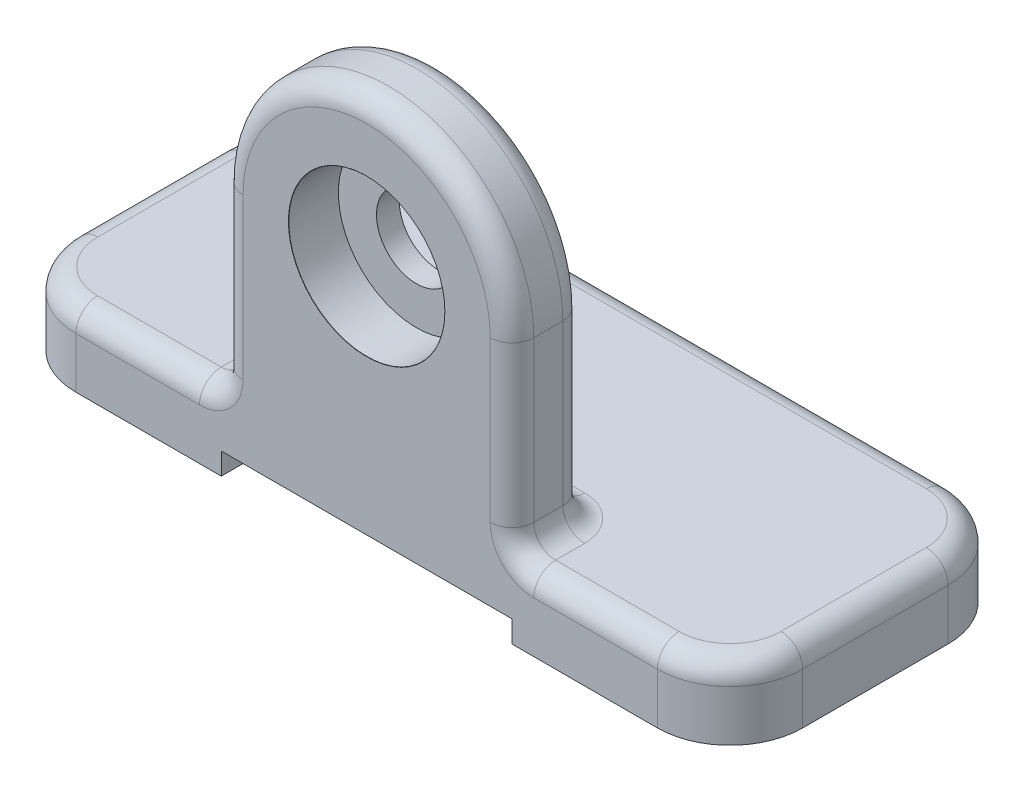
SolidWorks part; units mm, degrees
ref_plane "정면" through (0, 0, 0) normal (0, 0, 1) x (1, 0, 0)
ref_plane "윗면" through (0, 0, 0) normal (0, 1, 0) x (1, 0, 0)
ref_plane "우측면" through (0, 0, 0) normal (1, 0, 0) x (0, 0, -1)
sketch "Sketch3" plane through (0, 0, 0) normal (0, 1, 0) x (1, 0, 0)
  line L1 (-50, 0) -> (50, 0)
  line L2 (-50, 0) -> (-50, 40)
  line L3 (-50, 40) -> (50, 40)
  line L4 (50, 0) -> (50, 40)
  point P4 (0, 0)
  dimension "D1" = 40
  dimension "D2" = 100
extrude "Boss-Extrude1" add sketch "Sketch3" along normal blind 10
sketch "Sketch4" plane through (0, 0, 0) normal (0, 0, 1) x (1, 0, 0)
  line L0 (-20, 0) -> (-20, 35)
  line L1 (-50, 0) -> (50, 0) construction
  line L2 (20, 35) -> (20, 0)
  line L3 (20, 0) -> (-20, 0)
  arc A0 (-20, 35) -> (20, 35) centre (0, 35) cw
  point P6 (0, 0)
  dimension "D1" = 20
  dimension "D2" = 35
extrude "Boss-Extrude2" add sketch "Sketch4" against normal blind 10
sketch "Sketch5" plane through (0, 0, 0) normal (0, 0, 1) x (1, 0, 0)
  line L0 (-50, 0) -> (50, 0) construction
  line L1 (-20, 3) -> (20, 3)
  line L2 (-20, 3) -> (-20, 0)
  line L3 (-20, 0) -> (20, 0)
  line L4 (20, 3) -> (20, 0)
  line L5 (-20, 35) -> (-20, 10) construction
  line L6 (20, 10) -> (20, 35) construction
  dimension "D1" = 3
extrude "Cut-Extrude1" cut sketch "Sketch5" against normal through all
hole_wizard "CBORE for M10 Hex Head Bolt1" positions "3DSketch1" profile "Sketch6" counterbore size "M10" standard "Ansi Metric" end condition through all
sketch3d "3DSketch1"
  line L0 (0, 35, -10) -> (0, 35, 0) construction
  point P0 (0, 35, 0)
sketch "Sketch6" plane through (0, 35, 0) normal (1, 0, 0) x (0, -1, 0)
  line L0 (0, 0) -> (0, 40)
  line L1 (0, 40) -> (5.5, 40)
  line L3 (5.5, 40) -> (5.5, 6.85)
  line L4 (10.74, 6.85) -> (5.5, 6.85)
  line L5 (10.74, 6.85) -> (10.74, 0.025)
  line L6 (10.74, 0.025) -> (10.765, 0)
  line L7 (10.765, 0) -> (0, 0)
  line L8 (-10.74, 0.025) -> (-10.765, 0) construction
  line L11 (0, -6.35) -> (0, 107.95) construction
  dimension "관통 구멍 지름" = 11
  dimension "관통 구멍 깊이" = 40
  dimension "카운터보어 지름" = 21.48
  dimension "카운터보어 깊이" = 6.85
  dimension "표면 카운터싱크 지름" = 21.53
  dimension "표면 카운터싱크 각도" = 90
fillet "Fillet1" radius 10 4 edges at (50, 5, -40) (50, 5, 0) (-50, 5, 0) (-50, 5, -40)
fillet "Fillet2" radius 3 18 edges at (-20, 22.5, 0) (-20, 22.5, -10) (0, 55, 0) (0, 55, -10) (20, 22.5, -10) (20, 22.5, 0) (20, 10, -5) (0, 10, -10) (30, 10, 0) (47.0711, 10, -2.9289) (50, 10, -20) (47.0711, 10, -37.0711) (0, 10, -40) (-47.0711, 10, -37.0711) (-50, 10, -20) (-47.0711, 10, -2.9289) (-20, 10, -5) (-30, 10, 0)
